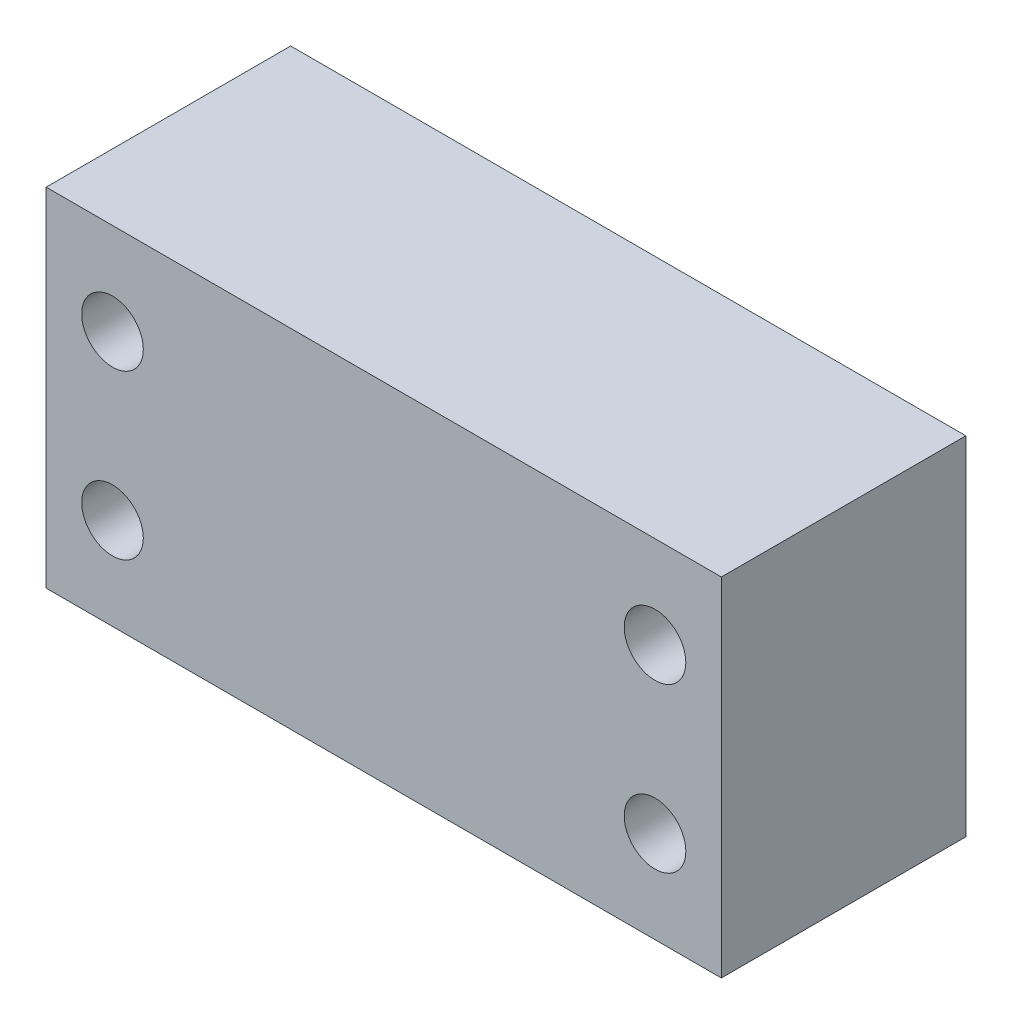
SolidWorks part; units mm, degrees
ref_plane "Front Plane" through (0, 0, 0) normal (0, 0, 1) x (1, 0, 0)
ref_plane "Top Plane" through (0, 0, 0) normal (0, 1, 0) x (1, 0, 0)
ref_plane "Right Plane" through (0, 0, 0) normal (1, 0, 0) x (0, 0, -1)
sketch "Sketch1" plane through (0, 0, 0) normal (0, 0, 1) x (1, 0, 0)
  line L1 (-18.0975, 9.3091) -> (18.0975, 9.3091)
  line L2 (-18.0975, 9.3091) -> (-18.0975, -9.3091)
  line L3 (-18.0975, -9.3091) -> (18.0975, -9.3091)
  line L4 (18.0975, 9.3091) -> (18.0975, -9.3091)
  line L5 (-18.0975, 9.3091) -> (18.0975, -9.3091) construction
  line L6 (-18.0975, -9.3091) -> (18.0975, 9.3091) construction
  point P0 (0, 0)
  dimension "D1" = 18.6182
  dimension "D2" = 36.195
extrude "Boss-Extrude1" add sketch "Sketch1" along normal blind 13.1064
sketch "Sketch4" plane through (0, 0, 13.1064) normal (0, 0, 1) x (1, 0, 0)
  line L0 (18.0975, 9.3091) -> (-18.0975, 9.3091) construction
  line L1 (0, 9.3091) -> (0, -9.3091) construction
  line L2 (-18.0975, -9.3091) -> (18.0975, -9.3091) construction
  line L3 (-18.0975, 0) -> (18.0975, 0) construction
  line L4 (-18.0975, 9.3091) -> (-18.0975, -9.3091) construction
  line L5 (18.0975, -9.3091) -> (18.0975, 9.3091) construction
  circle A0 centre (-14.5415, 4.3815) radius 1.651
  circle A4 centre (14.5415, 4.3815) radius 1.651
  circle A5 centre (14.5415, -4.3815) radius 1.651
  circle A6 centre (-14.5415, -4.3815) radius 1.651
  dimension "D1" = 3.302
  dimension "D5" = 4.9276
  dimension "D2" = 3.556
extrude "Cut-Extrude1" cut sketch "Sketch4" against normal through all
equation "\"D5@Sketch4\"=0.129 + 0.13*0.5"
equation "\"D2@Sketch4\"=0.075+0.13*0.5"
